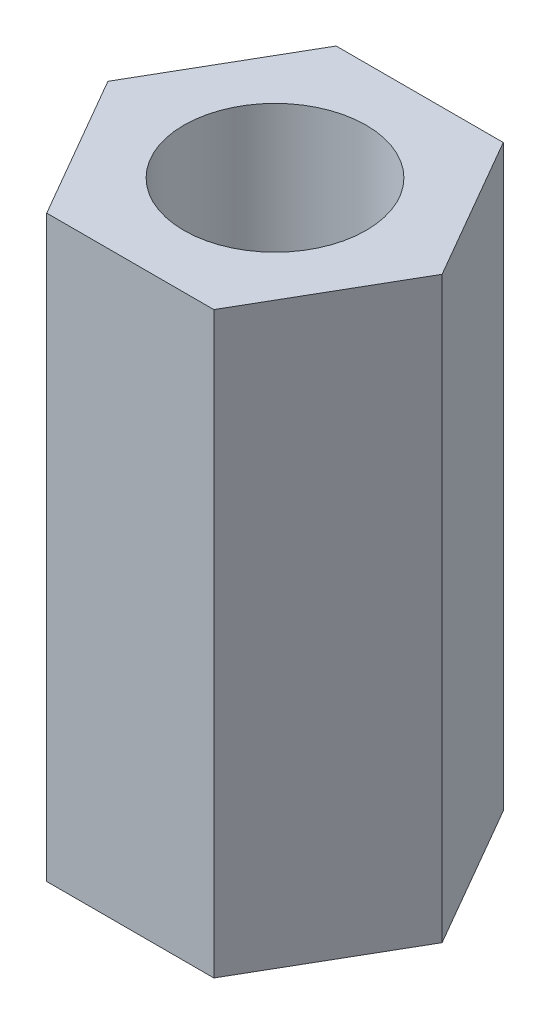
SolidWorks part; units mm, degrees
ref_plane "Спереди" through (0, 0, 0) normal (0, 0, 1) x (1, 0, 0)
ref_plane "Сверху" through (0, 0, 0) normal (0, 1, 0) x (1, 0, 0)
ref_plane "Справа" through (0, 0, 0) normal (1, 0, 0) x (0, 0, -1)
sketch "Эскиз1" plane through (0, 0, 0) normal (0, 1, 0) x (1, 0, 0)
  line L1 (2.8868, 0) -> (1.4434, 2.5)
  line L2 (1.4434, 2.5) -> (-1.4434, 2.5)
  line L3 (-1.4434, 2.5) -> (-2.8868, 0)
  line L4 (-2.8868, 0) -> (-1.4434, -2.5)
  line L5 (-1.4434, -2.5) -> (1.4434, -2.5)
  line L6 (1.4434, -2.5) -> (2.8868, 0)
  circle A0 centre (0, 0) radius 2.5 construction
  dimension "D1" = 5
extrude "Бобышка-Вытянуть1" add sketch "Эскиз1" along normal blind 10
hole_wizard "Сверло под метчик  спиральное M36" positions "Эскиз16" profile "Эскиз17" hole size "M3x0.5" standard "DIN"
sketch "Эскиз16" plane through (0, 10, 0) normal (0, 1, 0) x (1, 0, 0)
  point P0 (0, 0)
sketch "Эскиз17" plane through (0, 10, 0) normal (1, 0, 0) x (0, 0, 1)
  line L0 (0, 0) -> (0, 4.9464)
  line L1 (0, 4.9464) -> (1.575, 4)
  line L2 (1.575, 4) -> (1.575, 0)
  line L5 (1.575, 0) -> (0, 0)
  line L10 (0, 4.9464) -> (-1.575, 4) construction
  line L11 (0, -6.35) -> (0, 107.95) construction
  dimension "Диаметр отверстия" = 3.15
  dimension "Глубина отверстия" = 4
  dimension "Угол заточки сверла" = 118
hole_wizard "Сверло под метчик  спиральное M36" positions "Эскиз18" profile "Эскиз19" hole size "M3x0.5" standard "DIN"
sketch "Эскиз18" plane through (0, 0, 0) normal (0, -1, 0) x (-1, 0, 0)
  point P0 (0, 0)
sketch "Эскиз19" plane through (0, 0, 0) normal (1, 0, 0) x (0, 0, -1)
  line L0 (0, 0) -> (0, 4.9464)
  line L1 (0, 4.9464) -> (1.575, 4)
  line L2 (1.575, 4) -> (1.575, 0)
  line L5 (1.575, 0) -> (0, 0)
  line L10 (0, 4.9464) -> (-1.575, 4) construction
  line L11 (0, -6.35) -> (0, 107.95) construction
  dimension "Диаметр отверстия" = 3.15
  dimension "Глубина отверстия" = 4
  dimension "Угол заточки сверла" = 118
